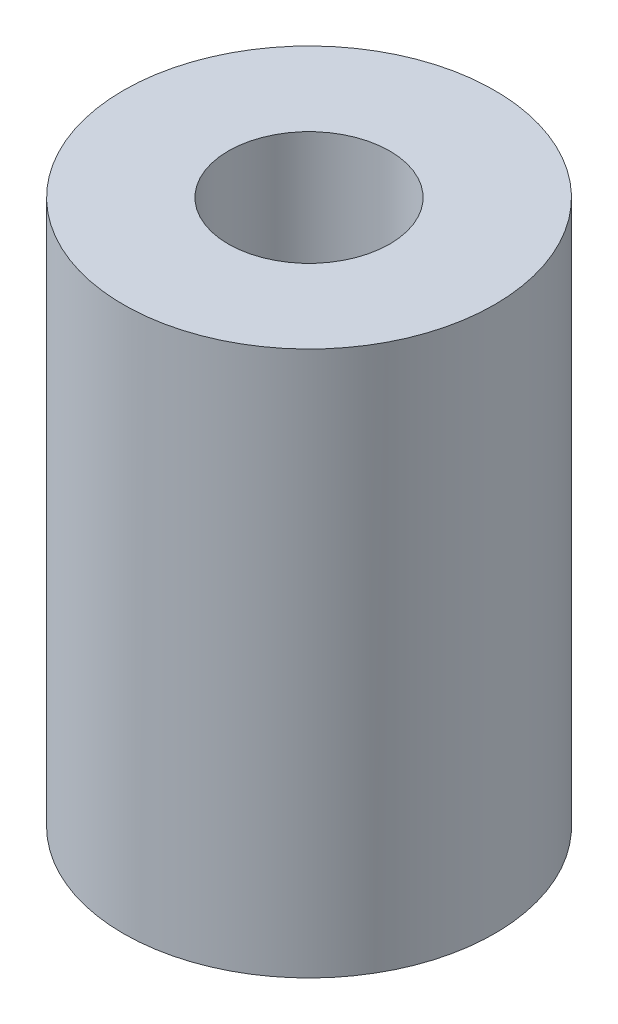
SolidWorks part; units mm, degrees
ref_plane "Спереди" through (0, 0, 0) normal (0, 0, 1) x (1, 0, 0)
ref_plane "Сверху" through (0, 0, 0) normal (0, 1, 0) x (1, 0, 0)
ref_plane "Справа" through (0, 0, 0) normal (1, 0, 0) x (0, 0, -1)
sketch "Эскиз1" plane through (0, 0, 0) normal (0, 1, 0) x (1, 0, 0)
  circle A0 centre (0, 0) radius 2
  circle A1 centre (0, 0) radius 4.6
extrude "Вытянуть1" add sketch "Эскиз1" along normal up to surface (13.5 mm away)
